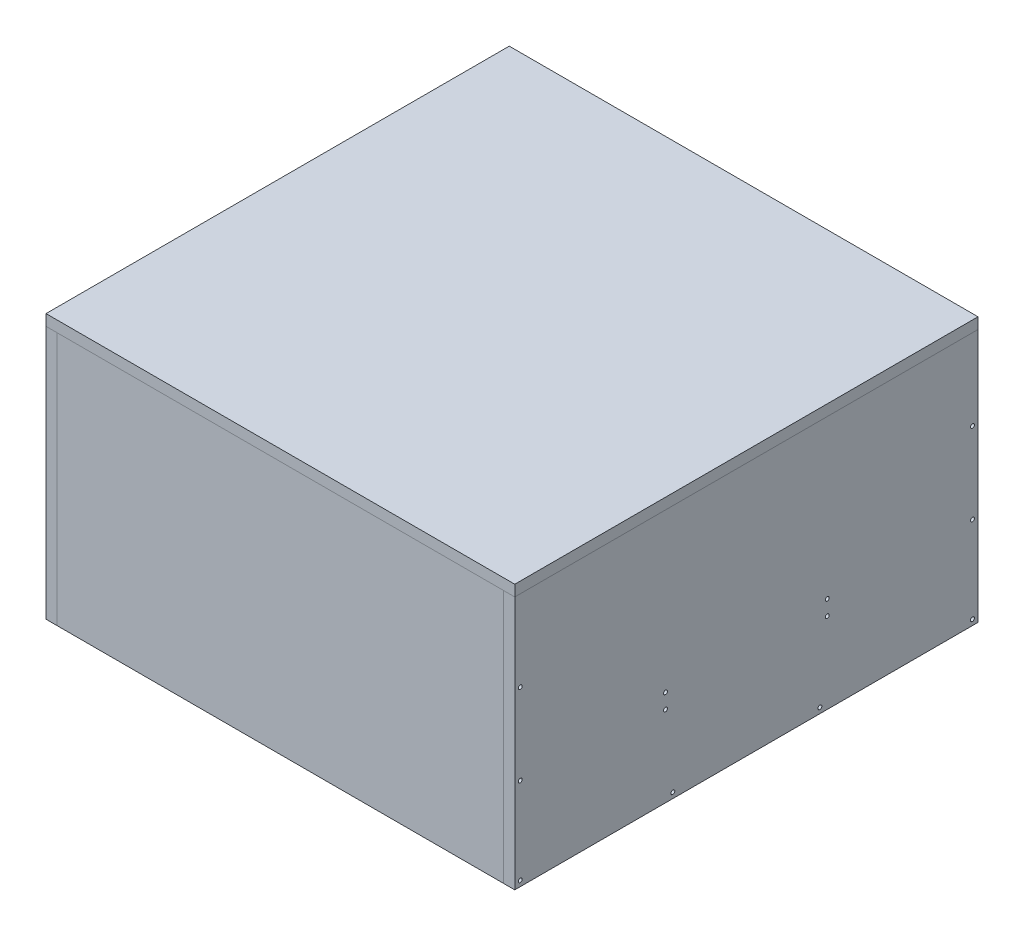
SolidWorks part; units mm, degrees
ref_plane "Front Plane" through (0, 0, 0) normal (0, 0, 1) x (1, 0, 0)
ref_plane "Top Plane" through (0, 0, 0) normal (0, 1, 0) x (1, 0, 0)
ref_plane "Right Plane" through (0, 0, 0) normal (1, 0, 0) x (0, 0, -1)
sketch "Sketch1" plane through (0, 0, 0) normal (0, 1, 0) x (1, 0, 0)
  line L1 (0, 0) -> (257.175, 0)
  line L2 (0, 0) -> (0, 254)
  line L3 (0, 254) -> (257.175, 254)
  line L4 (257.175, 0) -> (257.175, 254)
  dimension "D1" = 257.175
  dimension "D2" = 254
extrude "Boss-Extrude1" add sketch "Sketch1" against normal blind 6.35
sketch "Sketch2" plane through (0, 0, 0) normal (0, 0, 1) x (1, 0, 0)
  line L0 (257.175, -6.35) -> (257.175, 0) construction
  line L1 (0, -6.35) -> (257.175, -6.35)
  line L2 (0, -6.35) -> (0, 139.7)
  line L3 (0, 139.7) -> (257.175, 139.7)
  line L4 (257.175, -6.35) -> (257.175, 139.7)
  dimension "D1" = 146.05
extrude "Boss-Extrude2" add sketch "Sketch2" along normal blind 6.35 separate body
sketch "Sketch3" plane through (0, 0, 0) normal (0, -1, 0) x (1, 0, 0)
  line L0 (0, -127) -> (-23.5534, -127)
  line L1 (0, -254) -> (0, 0) construction
  line L2 (0, -127) -> (0, -138.9854)
ref_plane "Plane2" through (0, 0, -127) normal (0, 0, -1) x (-1, 0, 0)
mirror "Mirror1" about plane through (0, 0, -127) normal (0, 0, -1) of bodies 102
sketch "Sketch4" plane through (0, 0, 0) normal (-1, 0, 0) x (0, 0, 1)
  line L1 (-260.35, -6.35) -> (6.35, -6.35)
  line L2 (-260.35, -6.35) -> (-260.35, 139.7)
  line L3 (-260.35, 139.7) -> (6.35, 139.7)
  line L4 (6.35, -6.35) -> (6.35, 139.7)
extrude "Boss-Extrude3" add sketch "Sketch4" along normal blind 6.35 separate body
sketch "Sketch5" plane through (0, -6.35, 0) normal (0, -1, 0) x (1, 0, 0)
  line L0 (128.5875, 0) -> (-138.2478, 0)
  line L1 (0, 0) -> (257.175, 0) construction
ref_plane "Plane3" through (128.5875, -6.35, 0) normal (-1, 0, 0) x (0, 0, 1)
mirror "Mirror2" about plane through (128.5875, -6.35, 0) normal (-1, 0, 0) of bodies 104
sketch "Sketch6" plane through (0, 0, 0) normal (0, -1, 0) x (1, 0, 0)
  line L0 (128.5875, 0) -> (128.5875, -254)
  line L1 (0, 0) -> (257.175, 0) construction
  line L2 (257.175, -254) -> (0, -254) construction
  line L4 (122.2375, 0) -> (134.9375, 0)
  line L5 (122.2375, 0) -> (122.2375, -254)
  line L6 (122.2375, -254) -> (134.9375, -254)
  line L7 (134.9375, 0) -> (134.9375, -254)
  line L8 (122.2375, 0) -> (134.9375, -254) construction
  line L9 (122.2375, -254) -> (134.9375, 0) construction
  point P6 (128.5875, -127)
  dimension "D1" = 12.7
extrude "Boss-Extrude4" add sketch "Sketch6" against normal blind 57.15 separate body contours L5 L6 L7 L4
sketch "Sketch8" plane through (0, 57.15, 0) normal (0, 1, 0) x (-1, 0, 0)
  line L0 (-128.5875, -254) -> (-128.5875, -173.5667) construction
  line L2 (-122.2375, -254) -> (-134.9375, -254) construction
  line L3 (-128.5875, 0) -> (-128.5875, -80.4333) construction
  line L4 (-122.2375, 0) -> (-134.9375, 0) construction
  line L5 (-122.2375, 0) -> (-122.2375, -254) construction
  line L6 (-134.9375, -86.7833) -> (-122.2375, -86.7833)
  line L7 (-134.9375, -86.7833) -> (-134.9375, -74.0833)
  line L8 (-134.9375, -74.0833) -> (-122.2375, -74.0833)
  line L9 (-122.2375, -86.7833) -> (-122.2375, -74.0833)
  line L10 (-134.9375, -86.7833) -> (-122.2375, -74.0833) construction
  line L11 (-134.9375, -74.0833) -> (-122.2375, -86.7833) construction
  line L13 (-134.9375, -179.9167) -> (-122.2375, -179.9167)
  line L14 (-134.9375, -179.9167) -> (-134.9375, -167.2167)
  line L15 (-134.9375, -167.2167) -> (-122.2375, -167.2167)
  line L16 (-122.2375, -179.9167) -> (-122.2375, -167.2167)
  line L17 (-134.9375, -179.9167) -> (-122.2375, -167.2167) construction
  line L18 (-134.9375, -167.2167) -> (-122.2375, -179.9167) construction
  dimension "D1" = 80.4333
  dimension "D2" = 12.7
extrude "Cut-Extrude1" cut sketch "Sketch8" against normal blind 25.4
sketch "Sketch11" plane through (0, 31.75, 0) normal (0, 1, 0) x (-1, 0, 0)
  line L0 (-134.9375, -173.5667) -> (-128.5875, -173.5667) construction
  line L1 (0, -179.9167) -> (-257.175, -179.9167)
  line L2 (0, -179.9167) -> (0, -167.2167)
  line L3 (0, -167.2167) -> (-257.175, -167.2167)
  line L4 (-257.175, -179.9167) -> (-257.175, -167.2167)
  line L5 (0, -179.9167) -> (-257.175, -167.2167) construction
  line L6 (0, -167.2167) -> (-257.175, -179.9167) construction
  line L7 (-134.9375, -167.2167) -> (-134.9375, -179.9167) construction
  line L9 (0, -254) -> (0, 0) construction
  line L10 (-128.5875, -167.2167) -> (-128.5875, -173.5667) construction
  point P0 (-128.5875, -173.5667)
  dimension "D1" = 12.7
  dimension "D2" = 6.35
extrude "Boss-Extrude6" add sketch "Sketch11" along normal blind 25.4 separate body
mirror "Mirror3" about plane through (0, 0, -127) normal (0, 0, -1) of bodies 113
ref_plane "Plane4" through (257.175, 0, 0) normal (1, 0, 0) x (0, 0, -1)
sketch "Sketch21" plane through (-6.35, 0, 0) normal (-1, 0, 0) x (0, 0, 1)
  line L0 (-80.4333, 31.75) -> (-80.4333, 40.132) construction
  line L2 (-86.7833, 31.75) -> (-74.0833, 31.75) construction
  line L3 (-80.4333, 57.15) -> (-80.4333, 48.768) construction
  line L4 (-74.0833, 57.15) -> (-86.7833, 57.15) construction
  line L5 (-127, 57.15) -> (-127, 14.4604) construction
  line L6 (-86.7833, 57.15) -> (-167.2167, 57.15) construction
  line L7 (-173.5667, 31.75) -> (-173.5667, 40.132) construction
  line L8 (-173.5667, 57.15) -> (-173.5667, 48.768) construction
  line L9 (-257.175, 139.7) -> (-257.175, 93.1333) construction
  line L10 (-260.35, 139.7) -> (-254, 139.7) construction
  line L11 (-257.175, 0) -> (-257.175, 46.5667) construction
  line L12 (-254, -3.175) -> (-257.175, -3.175) construction
  line L13 (-254, -6.35) -> (-254, 0) construction
  line L14 (0, -3.175) -> (3.175, -3.175) construction
  line L15 (3.175, 0) -> (3.175, 46.5667) construction
  line L16 (3.175, 139.7) -> (3.175, 93.1333) construction
  line L17 (-254, -3.175) -> (-169.3418, -3.175) construction
  line L18 (0, -3.175) -> (-84.6582, -3.175) construction
  dimension "D1" = 8.382
  dimension "D2" = 46.5667
  dimension "D3" = 84.6582
hole_wizard "#4-40 Tapped Hole3" positions "3DSketch5" profile "Sketch23" tap size "#4-40" standard "Ansi Inch" end condition through all
sketch3d "3DSketch5"
  point P0 (-6.35, 93.1333, -257.175)
  point P3 (-6.35, 46.5667, -257.175)
  point P6 (-6.35, -3.175, -257.175)
  point P9 (-6.35, -3.175, -169.3418)
  point P12 (-6.35, -3.175, -84.6582)
  point P15 (-6.35, 40.132, -173.5667)
  point P18 (-6.35, 48.768, -173.5667)
  point P21 (-6.35, 48.768, -80.4333)
  point P24 (-6.35, 40.132, -80.4333)
  point P27 (-6.35, 46.5667, 3.175)
  point P30 (-6.35, 93.1333, 3.175)
  point P33 (-6.35, -3.175, 3.175)
sketch "Sketch23" plane through (-6.35, 93.1333, -257.175) normal (0, 1, 0) x (0, 0, 1)
  line L0 (0, 0) -> (0, 269.875)
  line L1 (0, 269.875) -> (1.1303, 269.875)
  line L2 (1.1303, 269.875) -> (1.1303, 0)
  line L5 (1.1303, 0) -> (0, 0)
  line L11 (0, -6.35) -> (0, 107.95) construction
  dimension "Thread Major Dia." = 2.2606
  dimension "Thru Tap Drill Depth" = 269.875
sketch "Sketch24" plane through (0, 0, 0) normal (0, 0, 1) x (1, 0, 0)
  line L0 (128.5875, 57.15) -> (128.5875, 40.2167) construction
  line L1 (122.2375, 57.15) -> (134.9375, 57.15) construction
  line L2 (128.5875, 140.4094) -> (128.5875, -153.1094) construction
  line L3 (128.5875, 0) -> (128.5875, 16.9333) construction
  line L4 (0, 0) -> (257.175, 0) construction
  dimension "D1" = 16.9333
hole_wizard "#4-40 Tapped Hole4" positions "3DSketch6" profile "Sketch25" tap size "#4-40" standard "Ansi Inch" end condition through all
sketch3d "3DSketch6"
  point P0 (128.5875, 40.2167, 0)
  point P3 (128.5875, 16.9333, 0)
sketch "Sketch25" plane through (128.5875, 40.2167, 0) normal (1, 0, 0) x (0, -1, 0)
  line L0 (0, 0) -> (0, 260.35)
  line L1 (0, 260.35) -> (1.1303, 260.35)
  line L2 (1.1303, 260.35) -> (1.1303, 0)
  line L5 (1.1303, 0) -> (0, 0)
  line L11 (0, -6.35) -> (0, 107.95) construction
  dimension "Thread Major Dia." = 2.2606
  dimension "Thru Tap Drill Depth" = 260.35
sketch "Sketch26" plane through (0, 139.7, 0) normal (0, 1, 0) x (-1, 0, 0)
  line L1 (6.35, 6.35) -> (-263.525, 6.35)
  line L2 (6.35, 6.35) -> (6.35, -260.35)
  line L3 (6.35, -260.35) -> (-263.525, -260.35)
  line L4 (-263.525, 6.35) -> (-263.525, -260.35)
extrude "Boss-Extrude7" add sketch "Sketch26" along normal blind 6.35 separate body
